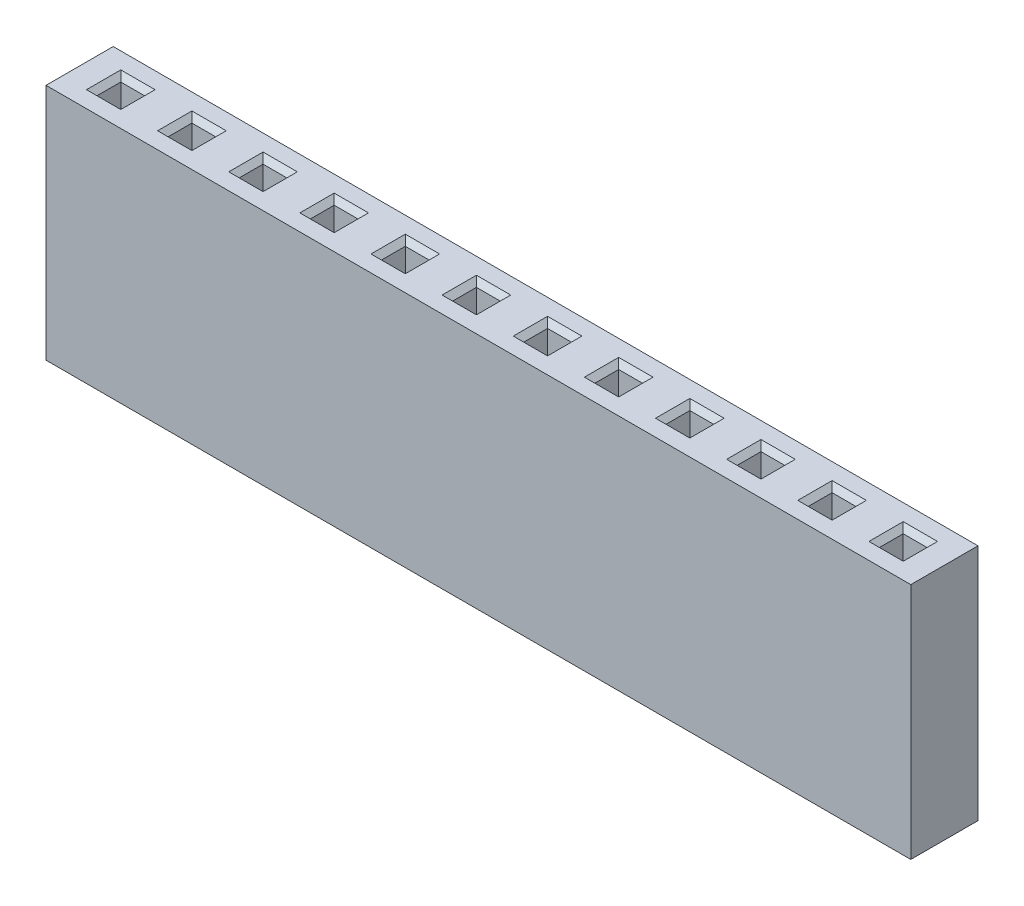
SolidWorks part; units mm, degrees
ref_plane "Front Plane" through (0, 0, 0) normal (0, 0, 1) x (1, 0, 0)
ref_plane "Top Plane" through (0, 0, 0) normal (0, 1, 0) x (1, 0, 0)
ref_plane "Right Plane" through (0, 0, 0) normal (1, 0, 0) x (0, 0, -1)
sketch "Sketch1" plane through (0, 0, 0) normal (0, 0, 1) x (1, 0, 0)
  line L1 (-15.44, -4.25) -> (15.44, -4.25)
  line L2 (-15.44, -4.25) -> (-15.44, 4.25)
  line L3 (-15.44, 4.25) -> (15.44, 4.25)
  line L4 (15.44, -4.25) -> (15.44, 4.25)
  line L5 (-15.44, -4.25) -> (15.44, 4.25) construction
  line L6 (-15.44, 4.25) -> (15.44, -4.25) construction
  point P0 (0, 0)
  dimension "D1" = 30.88
  dimension "D2" = 8.5
extrude "Boss-Extrude1" add sketch "Sketch1" along normal blind 2.4
sketch "Sketch2" plane through (0, 4.25, 0) normal (0, 1, 0) x (1, 0, 0)
  line L0 (-15.44, -1.2) -> (15.44, -1.2) construction
  line L1 (-15.44, -2.4) -> (-15.44, 0) construction
  line L2 (15.44, -2.4) -> (15.44, 0) construction
  line L4 (-14.395, -1.625) -> (-13.545, -1.625)
  line L5 (-14.395, -1.625) -> (-14.395, -0.775)
  line L6 (-14.395, -0.775) -> (-13.545, -0.775)
  line L7 (-13.545, -1.625) -> (-13.545, -0.775)
  line L8 (-14.395, -1.625) -> (-13.545, -0.775) construction
  line L9 (-14.395, -0.775) -> (-13.545, -1.625) construction
  point P6 (-13.97, -1.2)
  dimension "D1" = 0.85
  dimension "D2" = 0.85
  dimension "D3" = 1.47
extrude "Cut-Extrude1" cut sketch "Sketch2" against normal through all
chamfer "Chamfer1" distance 0.1875 4 edges at (-13.545, 4.25, 1.2) (-13.97, 4.25, 1.625) (-14.395, 4.25, 1.2) (-13.97, 4.25, 0.775)
pattern_linear "LPattern1" count 12 spacing 2.54 along (1, 0, 0) of "Chamfer1", "Cut-Extrude1"
